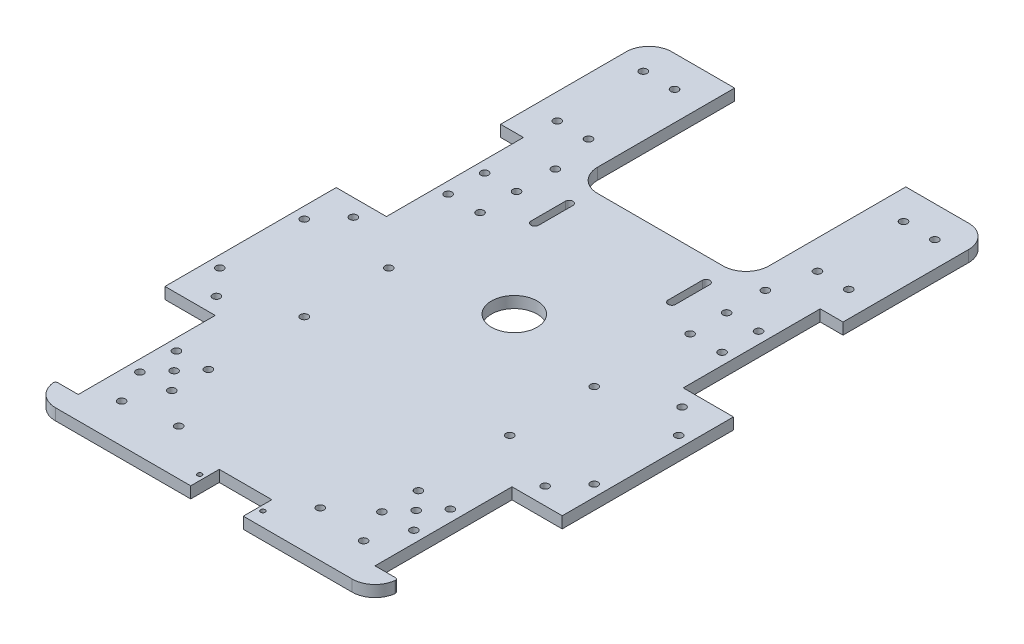
SolidWorks part; units mm, degrees
ref_plane "前视基准面" through (0, 0, 0) normal (0, 0, 1) x (1, 0, 0)
ref_plane "上视基准面" through (0, 0, 0) normal (0, 1, 0) x (1, 0, 0)
ref_plane "右视基准面" through (0, 0, 0) normal (1, 0, 0) x (0, 0, -1)
sketch "草图1" plane through (0, 0, 0) normal (0, 1, 0) x (1, 0, 0)
  line L27 (-43.8591, 198.0807) -> (-16.3591, 198.0807)
  line L59 (86.1409, 198.0807) -> (58.6409, 198.0807)
  line L70 (15.4159, -71.9193) -> (15.4159, -59.4193)
  line L72 (38.4459, -71.9193) -> (38.4459, -59.4193)
  line L73 (15.4159, -59.4193) -> (38.4459, -59.4193)
  line L77 (86.1409, 133.0807) -> (96.1409, 133.0807)
  line L78 (96.1409, 133.0807) -> (96.1409, 188.0807)
  line L80 (-43.8591, 133.0807) -> (-53.8591, 133.0807)
  line L81 (-53.8591, 133.0807) -> (-53.8591, 188.0807)
  line L83 (86.1409, 133.0807) -> (86.1409, 73.0807)
  line L84 (86.1409, 73.0807) -> (108.1409, 73.0807)
  line L86 (-43.8591, 133.0807) -> (-43.8591, 73.0807)
  line L87 (-43.8591, 73.0807) -> (-65.8591, 73.0807)
  line L89 (108.1409, -1.9193) -> (108.1409, 73.0807)
  line L91 (-65.8591, -1.9193) -> (-43.8591, -1.9193)
  line L92 (108.1409, -1.9193) -> (86.1409, -1.9193)
  line L94 (-65.8591, -1.9193) -> (-65.8591, 73.0807)
  line L96 (48.6409, 128.0807) -> (-6.3591, 128.0807)
  line L98 (58.6409, 138.0807) -> (58.6409, 198.0807)
  line L99 (-16.3591, 198.0807) -> (-16.3591, 138.0807)
  line L104 (15.4159, -71.9193) -> (-43.8591, -71.9193)
  line L105 (38.4459, -71.9193) -> (86.1409, -71.9193)
  line L106 (-52.8034, -61.9193) -> (-43.8591, -61.9193)
  line L108 (95.0852, -61.9193) -> (86.1409, -61.9193)
  line L110 (86.1409, -61.9193) -> (86.1409, -1.9193)
  line L111 (-43.8591, -61.9193) -> (-43.8591, -1.9193)
  arc A21 (-43.8591, 198.0807) -> (-53.8591, 188.0807) centre (-43.8591, 188.0807) ccw
  arc A59 (86.1409, 198.0807) -> (96.1409, 188.0807) centre (86.1409, 188.0807) cw
  circle A69 centre (13.0959, -65.6693) radius 1
  circle A70 centre (40.7659, -65.6693) radius 1
  circle A71 centre (66.1409, 17.0807) radius 1.65
  circle A72 centre (-60.8591, 54.0807) radius 1.65
  circle A73 centre (-23.8591, 54.0807) radius 1.65
  circle A74 centre (-23.8591, 17.0807) radius 1.65
  circle A75 centre (-60.8591, 17.0807) radius 1.65
  circle A76 centre (103.1409, 17.0807) radius 1.65
  circle A77 centre (103.1409, 54.0807) radius 1.65
  circle A78 centre (66.1409, 54.0807) radius 1.65
  circle A83 centre (-38.8591, 111.0807) radius 1.65
  circle A84 centre (-24.8591, 111.0807) radius 1.65
  circle A85 centre (-24.8591, 95.0807) radius 1.65
  circle A86 centre (-38.8591, 95.0807) radius 1.65
  circle A87 centre (-38.8591, -23.9193) radius 1.65
  circle A88 centre (-24.8591, -23.9193) radius 1.65
  circle A89 centre (-38.8591, -39.9193) radius 1.65
  circle A90 centre (-24.8591, -39.9193) radius 1.65
  circle A91 centre (-29.0091, 184.4307) radius 1.65
  circle A92 centre (-42.7091, 184.4307) radius 1.65
  circle A93 centre (-42.7091, 146.7307) radius 1.65
  circle A94 centre (-29.0091, 146.7307) radius 1.65
  circle A95 centre (-24.8591, 128.0807) radius 1.65
  circle A97 centre (-9.8591, -51.9193) radius 1.65
  circle A98 centre (52.1409, -51.9193) radius 1.65
  circle A99 centre (67.1409, -39.9193) radius 1.65
  circle A100 centre (81.1409, -39.9193) radius 1.65
  circle A101 centre (67.1409, -23.9193) radius 1.65
  circle A102 centre (81.1409, -23.9193) radius 1.65
  circle A103 centre (81.1409, 95.0807) radius 1.65
  circle A104 centre (67.1409, 95.0807) radius 1.65
  circle A105 centre (67.1409, 111.0807) radius 1.65
  circle A106 centre (81.1409, 111.0807) radius 1.65
  circle A107 centre (67.1409, 128.0807) radius 1.65
  circle A108 centre (71.2909, 146.7307) radius 1.65
  circle A109 centre (84.9909, 146.7307) radius 1.65
  circle A110 centre (84.9909, 184.4307) radius 1.65
  circle A111 centre (71.2909, 184.4307) radius 1.65
  circle A112 centre (21.1409, 64.0807) radius 10
  arc A113 (-6.3591, 128.0807) -> (-16.3591, 138.0807) centre (-6.3591, 138.0807) cw
  arc A114 (58.6409, 138.0807) -> (48.6409, 128.0807) centre (48.6409, 138.0807) cw
  arc A115 (86.1409, -71.9193) -> (96.079, -63.0304) centre (86.1409, -61.9193) ccw
  arc A116 (-43.8591, -71.9193) -> (-53.7972, -63.0304) centre (-43.8591, -61.9193) cw
  arc A117 (95.0852, -61.9193) -> (96.079, -63.0304) centre (95.0852, -62.9193) cw
  arc A118 (-52.8034, -61.9193) -> (-53.7972, -63.0304) centre (-52.8034, -62.9193) ccw
  point P70 (-53.8591, 198.0807)
  point P98 (96.1409, 198.0807)
  dimension "D10" = 37
  dimension "D12" = 3.3
  dimension "D17" = 37
  dimension "D18" = 19
  dimension "D19" = 19
  dimension "D20" = 19
  dimension "D25" = 16
  dimension "D27" = 10
  dimension "D30" = 16
  dimension "D34" = 13.7
  dimension "D28" = 2
  dimension "D38" = 14
  dimension "D21" = 3.3
  dimension "D39" = 92
  dimension "D44" = 20
  dimension "D45" = 2.32
  dimension "D29" = 1
  dimension "D47" = 27.67
  dimension "D48" = 22
  dimension "D49" = 22
  dimension "D50" = 22
  dimension "D9" = 37
  dimension "D8" = 10
  dimension "D11" = 37
  dimension "D15" = 37
  dimension "D16" = 37
  dimension "D23" = 16
  dimension "D24" = 14
  dimension "D26" = 16
  dimension "D37" = 14
  dimension "D40" = 14
  dimension "D51" = 22
  dimension "D42" = 14
  dimension "D31" = 16
  dimension "D43" = 16
  dimension "D53" = 16
  dimension "D54" = 14
  dimension "D55" = 14
  dimension "D57" = 22
  dimension "D59" = 22
  dimension "D5" = 60
  dimension "D6" = 150
  dimension "D7" = 37.5
  dimension "D13" = 14
  dimension "D14" = 16
  dimension "D22" = 19
  dimension "D32" = 37
  dimension "D33" = 37
  dimension "D35" = 37.7
  dimension "D36" = 13.65
  dimension "D41" = 62
  dimension "D46" = 2.32
  dimension "D52" = 5.725
  dimension "D56" = 22
  dimension "D58" = 22
extrude "凸台-拉伸2" add sketch "草图1" along normal blind 5
ref_plane "基准面1" through (21.1409, 0, 0) normal (-1, 0, 0) x (0, 0, 1)
sketch "草图2" plane through (0, 5, 0) normal (0, 1, 0) x (1, 0, 0)
  line L6 (52.7909, 118.0807) -> (52.7909, 103.0807)
  line L8 (49.4909, 118.0807) -> (49.4909, 103.0807)
  line L9 (86.1409, 198.0807) -> (58.6409, 198.0807) construction
  line L10 (21.1409, 2.75) -> (21.1409, -2.75) construction
  line L11 (-7.2091, 118.0807) -> (-7.2091, 103.0807)
  line L12 (-10.5091, 118.0807) -> (-10.5091, 103.0807)
  arc A1 (52.7909, 118.0807) -> (49.4909, 118.0807) centre (51.1409, 118.0807) ccw
  arc A2 (52.7909, 103.0807) -> (49.4909, 103.0807) centre (51.1409, 103.0807) cw
  circle A3 centre (21.1409, 64.0807) radius 10 construction
  arc A4 (-10.5091, 103.0807) -> (-7.2091, 103.0807) centre (-8.8591, 103.0807) ccw
  arc A5 (-10.5091, 118.0807) -> (-7.2091, 118.0807) centre (-8.8591, 118.0807) cw
  dimension "D2" = 30
  dimension "D3" = 1.65
  dimension "D1" = 3.3
  dimension "D4" = 15
  dimension "D5" = 80
extrude "切除-拉伸1" cut sketch "草图2" against normal up to surface (5 mm away) up to face at (21.8221, 0, -51.005)
sketch "草图4" plane through (0, 0, 0) normal (0, -1, 0) x (1, 0, 0)
  circle A0 centre (-31.8591, 31.9193) radius 1.65
  circle A1 centre (-31.8591, 54.9193) radius 1.65
  circle A2 centre (74.1409, 31.9193) radius 1.65
  circle A3 centre (74.1409, 54.9193) radius 1.65
  circle A4 centre (81.1409, 23.9193) radius 1.65 construction
  circle A5 centre (81.1409, 39.9193) radius 1.65 construction
  circle A6 centre (-38.8591, 23.9193) radius 1.65 construction
  circle A7 centre (-38.8591, 39.9193) radius 1.65 construction
  dimension "D3" = 3.3
  dimension "D4" = 3.3
  dimension "D5" = 3.3
  dimension "D6" = 3.3
  dimension "D1" = 8
  dimension "D2" = 15
  dimension "D7" = 8
  dimension "D8" = 15
extrude "切除-拉伸3" cut sketch "草图4" against normal up to surface (5 mm away) up to face at (51.1409, 5, -110.5807)
sketch "草图5" plane through (0, 0, 0) normal (0, -1, 0) x (1, 0, 0)
  line L0 (108.1409, 1.9193) -> (108.1409, -73.0807) construction
  line L1 (108.1409, -73.0807) -> (86.1409, -73.0807) construction
  line L3 (21.1409, 2.75) -> (21.1409, -2.75) construction
  circle A0 centre (93.1409, -65.5807) radius 1.65
  circle A1 centre (93.1409, -5.5807) radius 1.65
  circle A2 centre (-50.8591, -5.5807) radius 1.65
  circle A3 centre (-50.8591, -65.5807) radius 1.65
  dimension "D2" = 15
  dimension "D3" = 60
  dimension "D4" = 3.3
  dimension "D5" = 3.3
  dimension "D6" = 7.5
  dimension "D1" = 15
extrude "切除-拉伸4" cut sketch "草图5" against normal up to surface (5 mm away) up to face at (-31.8591, 5, 56.5693)
